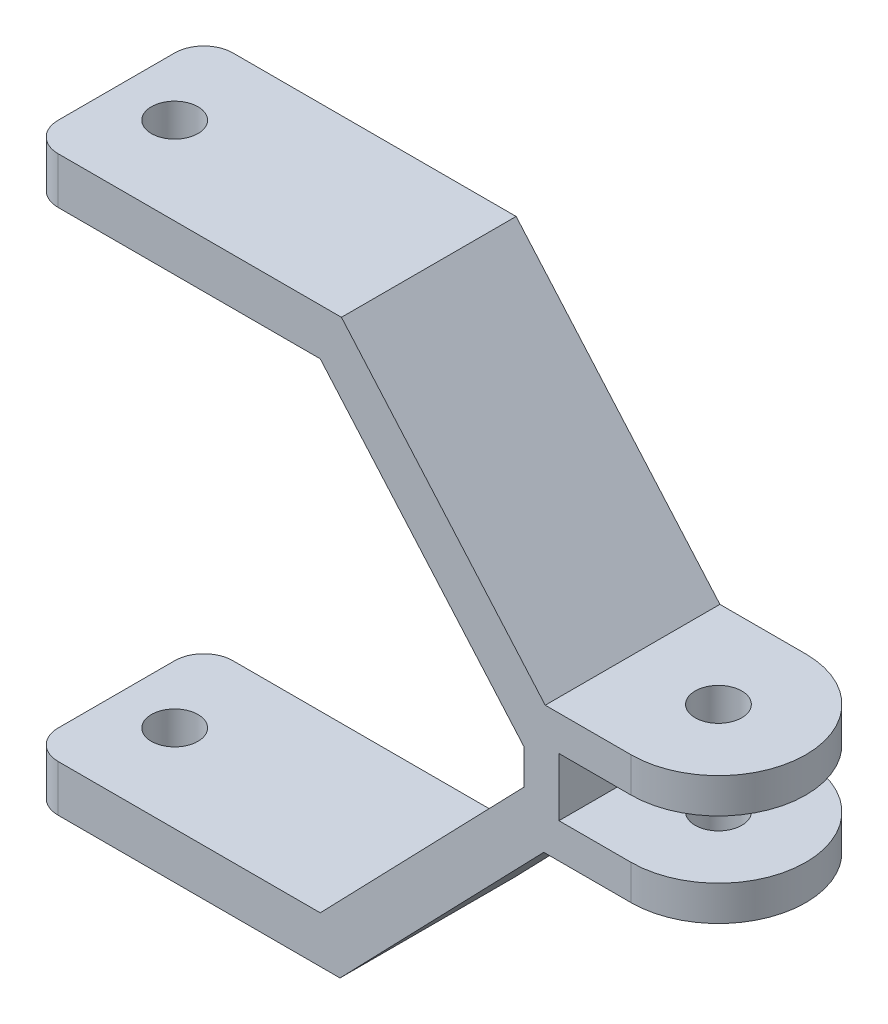
SolidWorks part; units mm, degrees
ref_plane "前基準面" through (0, 0, 0) normal (0, 0, 1) x (1, 0, 0)
ref_plane "上基準面" through (0, 0, 0) normal (0, 1, 0) x (1, 0, 0)
ref_plane "右基準面" through (0, 0, 0) normal (1, 0, 0) x (0, 0, -1)
sketch "草圖1" plane through (0, 0, 0) normal (0, 0, 1) x (1, 0, 0)
  line L0 (-26.6965, 45.2) -> (-47.6965, 45.2)
  line L1 (-25, 0) -> (-51.6965, 0)
  line L2 (0, 18.1) -> (0, 21.1)
  line L3 (-24.8754, 49.2) -> (-51.6965, 49.2)
  line L4 (-51.6965, 0) -> (-51.6965, 4)
  line L5 (-24.8754, 49.2) -> (-7.3754, 29.1)
  line L6 (-7.5, 18.1) -> (-25, 0)
  line L7 (-7.3754, 29.1) -> (0, 29.1)
  line L8 (-7.5, 18.1) -> (0, 18.1)
  line L9 (0, 26.1) -> (0, 29.1)
  line L10 (-26.6965, 4) -> (-47.6965, 4)
  line L11 (-9.1965, 22.1) -> (-26.6965, 4)
  line L12 (-47.6965, 45.2) -> (-51.6965, 45.2)
  line L13 (0, 26.1) -> (-6.1965, 26.1)
  line L14 (-51.6965, 4) -> (-47.6965, 4)
  line L15 (-26.6965, 45.2) -> (-9.1965, 25.1)
  line L16 (-9.1965, 25.1) -> (-9.1965, 22.1)
  line L17 (-51.6965, 45.2) -> (-51.6965, 49.2)
  line L18 (-9.1965, 22.1) -> (-4, 22.1) construction
  line L19 (-9.1965, 25.1) -> (-4, 25.1) construction
  line L20 (-4, 22.1) -> (-4, 25.1) construction
  line L21 (-47.6965, 4) -> (-47.6965, 45.2) construction
  line L22 (-51.6965, 0) -> (-51.6965, 49.2) construction
  line L24 (0, 21.1) -> (-6.1965, 21.1)
  line L25 (-6.1965, 26.1) -> (-6.1965, 21.1)
  line L26 (0, 18.1) -> (0, 29.1) construction
  dimension "D4" = 25
  dimension "D1" = 41.2
  dimension "D2" = 4
  dimension "D3" = 17.5
  dimension "D7" = 3
  dimension "D8" = 3
  dimension "D9" = 3
extrude "填料-伸長1" add sketch "草圖1" along normal blind 15
sketch "草圖2" plane through (0, 0, 0) normal (0, -1, 0) x (1, 0, 0)
  line L0 (-51.6965, 15) -> (-51.6965, 0) construction
  line L1 (-51.6965, 15) -> (-25, 15) construction
  circle A0 centre (-46.6965, 7.5) radius 2
  dimension "D1" = 5
  dimension "D2" = 7.5
  dimension "D3" = 4
extrude "除料-伸長1" cut sketch "草圖2" against normal up to surface (49.2 mm away) up to face at (-38.286, 49.2, 7.5)
sketch "草圖3" plane through (0, 18.1, 0) normal (0, -1, 0) x (1, 0, 0)
  line L0 (0, 15) -> (0, 0) construction
  circle A0 centre (0, 7.5) radius 7.5
extrude "填料-伸長2" add sketch "草圖3" against normal blind 3
sketch "草圖4" plane through (0, 29.1, 0) normal (0, 1, 0) x (1, 0, 0)
  line L0 (0, -15) -> (0, 0) construction
  circle A0 centre (0, -7.5) radius 7.5
extrude "填料-伸長3" add sketch "草圖4" against normal blind 3
sketch "草圖5" plane through (0, 29.1, 0) normal (0, 1, 0) x (1, 0, 0)
  circle A0 centre (0, -7.5) radius 2
  dimension "D1" = 4
extrude "除料-伸長2" cut sketch "草圖5" against normal blind 11
fillet "圓角1" radius 2.5 4 edges at (-51.6965, 2, 0) (-51.6965, 47.2, 15) (-51.6965, 47.2, 0) (-51.6965, 2, 15)
